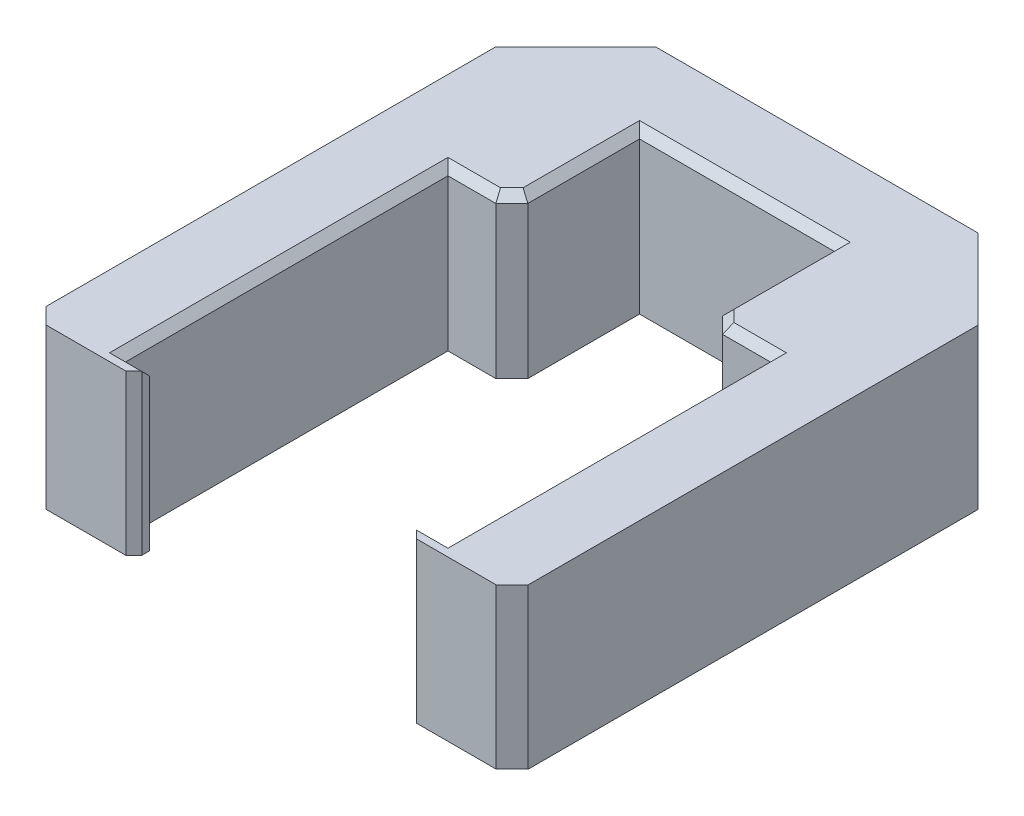
SolidWorks part; units mm, degrees
ref_plane "Front Plane" through (0, 0, 0) normal (0, 0, 1) x (1, 0, 0)
ref_plane "Top Plane" through (0, 0, 0) normal (0, 1, 0) x (1, 0, 0)
ref_plane "Right Plane" through (0, 0, 0) normal (1, 0, 0) x (0, 0, -1)
sketch "Sketch1" plane through (0, 0, 0) normal (0, 1, 0) x (1, 0, 0)
  line L0 (10, -980) -> (10, 49020) construction
  line L1 (0, 0) -> (20, 0) construction
  line L2 (0, 0) -> (0, 20) construction
  line L3 (0, 20) -> (4, 20) construction
  line L4 (20, 0) -> (20, 20) construction
  line L5 (16, 20) -> (20, 20) construction
  line L7 (4, 20) -> (4, 28) construction
  line L8 (4, 28) -> (16, 28) construction
  line L9 (16, 20) -> (16, 28) construction
  line L10 (-1000, 10) -> (-5.1, 10) construction
  line L11 (-0.1, 0) -> (-0.1, 20.1)
  line L12 (-0.1, 20.1) -> (3.9, 20.1)
  line L13 (3.9, 20.1) -> (3.9, 28.1)
  line L14 (3.9, 28.1) -> (16.1, 28.1)
  line L15 (16.1, 20.1) -> (16.1, 28.1)
  line L16 (16.1, 20.1) -> (20.1, 20.1)
  line L17 (20.1, 0) -> (20.1, 20.1)
  line L18 (25.1, 10) -> (49000, 10) construction
  line L19 (-0.1, 10) -> (20.1, 10)
  line L20 (-5.1, 10) -> (-5.1, 33.1)
  line L21 (-5.1, 33.1) -> (25.1, 33.1)
  line L22 (25.1, 10) -> (25.1, 33.1)
  line L23 (-0.1, 10) -> (20.1, 10)
  line L24 (-5.1, 10) -> (-5.1, -1.0767)
  line L26 (25.1, 10) -> (25.1, -1.0767)
  line L27 (-0.1, 10) -> (20.1, 10) construction
  line L28 (0, -0.1) -> (1.4, -0.1)
  line L29 (-5.1, -1.0767) -> (1.4, -1.0767)
  line L30 (1.4, -1.0767) -> (1.4, -0.1)
  line L31 (1.4, -0.1) -> (-0.1, -0.1)
  line L32 (-0.1, -0.1) -> (-0.1, 0)
  line L33 (18.6, -0.1) -> (20.1, -0.1)
  line L34 (20.1, -0.1) -> (20.1, 0)
  line L35 (25.1, -1.0767) -> (18.6, -1.0767)
  line L36 (18.6, -1.0767) -> (18.6, -0.1)
  line L37 (18.6, -0.1) -> (20, -0.1)
  line L38 (0, -0.1) -> (20, -0.1) construction
  point P14 (0, 10)
  point P26 (-47.4669, 19.613)
  dimension "D1" = 20
  dimension "D2" = 20
  dimension "D3" = 8
  dimension "D4" = 12
  dimension "D5" = 6
  dimension "D7" = 5
  dimension "D8" = 5
  dimension "D9" = 5
  dimension "D11" = 6.5
  dimension "D6" = 0.1
  dimension "D10" = 0.1
extrude "Boss-Extrude1" add sketch "Sketch1" along normal blind 10 contours L19 L22 L21 L20 L11 L12 L13 L14 L15 L16 L17
chamfer "Chamfer1" distance 5 angle 45 2 edges at (25.1, 5, -33.1) (-5.1, 5, -33.1)
chamfer "Chamfer3" distance 1 angle 45 4 edges at (-5.1, 5, 1.0767) (25.1, 5, 1.0767) (16.1, 5, -20.1) (3.9, 5, -20.1)
chamfer "Chamfer4" distance 0.5 angle 45 13 edges at (18.6, 5, 0.1) (19.35, 10, 0.1) (18.6, 10, -20.1) (20.1, 10, -10) (1.4, 5, 0.1) (0.65, 10, 0.1) (1.4, 10, -20.1) (-0.1, 10, -10) (16.1, 10, -24.6) (10, 10, -28.1) (3.9, 10, -24.6) (16.6, 10, -20.6) (3.4, 10, -20.6)
chamfer "Chamfer5" distance 0.5 angle 45 2 edges at (18.6, 5, 1.0767) (1.4, 5, 1.0767)
